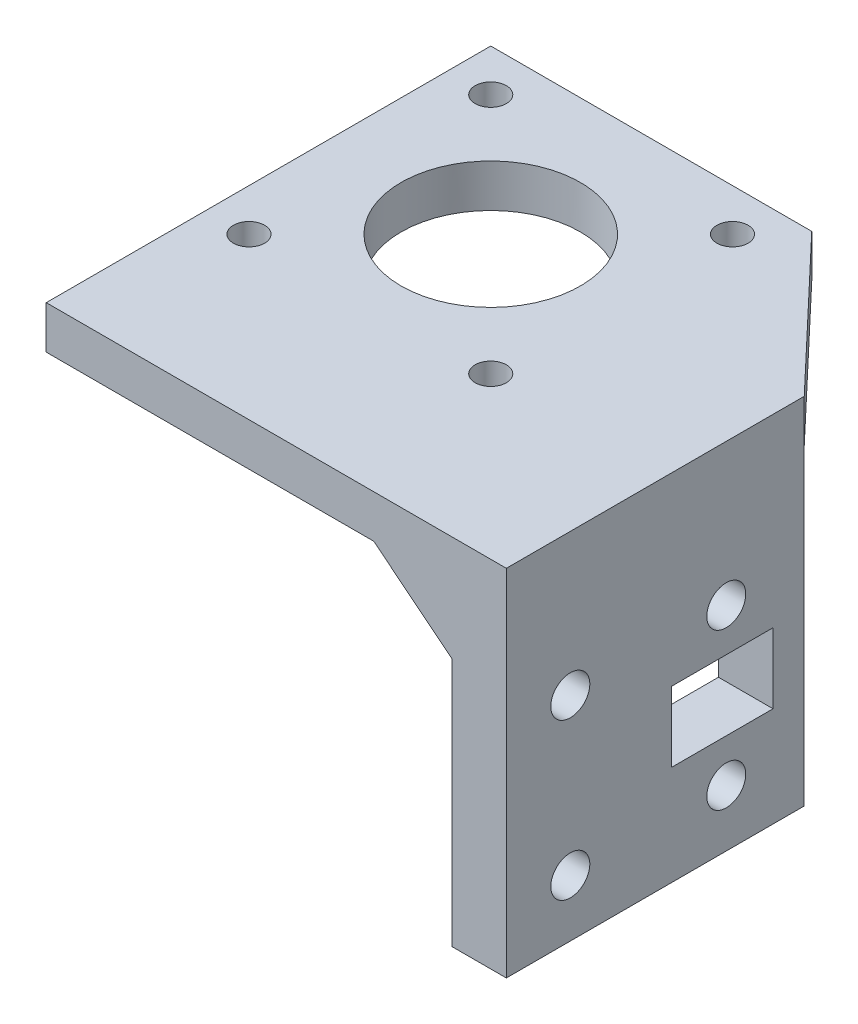
SolidWorks part; units mm, degrees
ref_plane "Front Plane" through (0, 0, 0) normal (0, 0, 1) x (1, 0, 0)
ref_plane "Top Plane" through (0, 0, 0) normal (0, 1, 0) x (1, 0, 0)
ref_plane "Right Plane" through (0, 0, 0) normal (1, 0, 0) x (0, 0, -1)
sketch "Sketch1" plane through (0, 0, 0) normal (0, 1, 0) x (1, 0, 0)
  line L1 (0, 0) -> (-59, 0)
  line L2 (0, 0) -> (0, -57)
  line L3 (0, -57) -> (-59, -57)
  line L4 (-59, 0) -> (-59, -57)
  point P5 (-59, 0)
  point P6 (0, 0)
  point P7 (0, 0)
  dimension "D1" = 57
  dimension "D2" = 59
extrude "Boss-Extrude1" add sketch "Sketch1" along normal blind 5.5
sketch "Sketch2" plane through (0, 5.5, 0) normal (0, 1, 0) x (1, 0, 0)
  line L0 (-59, 0) -> (-59, -57) construction
  line L1 (0, 0) -> (-59, 0) construction
  circle A0 centre (-53.6, -5.4) radius 2
  circle A1 centre (-22.6, -5.4) radius 2
  circle A2 centre (-53.6, -36.4) radius 2
  circle A3 centre (-22.6, -36.4) radius 2
  dimension "D5" = 31
  dimension "D9" = 4
  dimension "D10" = 4
  dimension "D11" = 4
  dimension "D12" = 4
  dimension "D8" = 31
  dimension "D1" = 5.4
  dimension "D2" = 5.4
  dimension "D3" = 5.4
  dimension "D4" = 31
  dimension "D6" = 5.4
  dimension "D7" = 31
extrude "Cut-Extrude1" cut sketch "Sketch2" against normal blind 10
sketch "Sketch4" plane through (0, 0, 0) normal (0, -1, 0) x (-1, 0, 0)
  line L0 (59, -57) -> (0, -57) construction
  line L1 (0, 0) -> (7, 0)
  line L2 (0, 0) -> (0, -57)
  line L3 (0, -57) -> (7, -57)
  line L4 (7, 0) -> (7, -57)
  dimension "D1" = 7
extrude "Boss-Extrude3" add sketch "Sketch4" along normal blind 40
sketch "Sketch5" plane through (-7, 0, 0) normal (-1, 0, 0) x (0, 0, 1)
  line L0 (57, -40) -> (57, 0) construction
  line L1 (57, -40) -> (0, -40) construction
  circle A0 centre (48.8, -32.7) radius 2.5
  circle A1 centre (48.8, -12.7) radius 2.5
  circle A2 centre (28.8, -32.7) radius 2.5
  circle A3 centre (28.8, -12.7) radius 2.5
  dimension "D3" = 5
  dimension "D4" = 5
  dimension "D7" = 5
  dimension "D8" = 5
  dimension "D1" = 8.2
  dimension "D2" = 7.3
  dimension "D5" = 20
  dimension "D6" = 0
  dimension "D9" = 20
  dimension "D10" = 20
  dimension "D11" = 20
  dimension "D12" = 7.3
extrude "Cut-Extrude2" cut sketch "Sketch5" against normal blind 33
sketch "Sketch6" plane through (-7, 0, 0) normal (-1, 0, 0) x (0, 0, 1)
  line L0 (57, 0) -> (0, 0) construction
  line L1 (0, -40) -> (18.8, -40)
  line L2 (0, -40) -> (0, 0)
  line L3 (0, 0) -> (18.8, 0)
  line L4 (18.8, -40) -> (18.8, 0)
  circle A0 centre (28.8, -32.7) radius 2.5 construction
  dimension "D1" = 10
extrude "Cut-Extrude3" cut sketch "Sketch6" against normal blind 33
sketch "Sketch7" plane through (0, 0, 0) normal (0, -1, 0) x (-1, 0, 0)
  line L0 (0, 0) -> (0, -18.8)
  line L1 (0, -18.8) -> (17.8364, 0)
  line L2 (0, 0) -> (59, 0) construction
  line L3 (17.8364, 0) -> (0, 0)
extrude "Cut-Extrude4" cut sketch "Sketch7" against normal blind 33
sketch "Sketch8" plane through (0, 0, 57) normal (0, 0, 1) x (1, 0, 0)
  line L0 (-7, 0) -> (-7, -8)
  line L1 (-7, -40) -> (-7, 0) construction
  line L2 (-7, -8) -> (-17, 0)
  line L3 (-59, 0) -> (-7, 0) construction
  line L4 (-17, 0) -> (-7, 0)
  dimension "D1" = 8
  dimension "D2" = 10
extrude "Boss-Extrude6" add sketch "Sketch8" against normal up to vertex (38.2 mm away) up to point (-7, -40, 18.8)
sketch "Sketch10" plane through (-7, 0, 0) normal (-1, 0, 0) x (0, 0, 1)
  line L1 (22.8, -18.2) -> (35.8, -18.2)
  line L2 (22.8, -18.2) -> (22.8, -27.2)
  line L3 (22.8, -27.2) -> (35.8, -27.2)
  line L4 (35.8, -18.2) -> (35.8, -27.2)
  line L5 (18.8, -40) -> (18.8, -8) construction
  circle A0 centre (28.8, -32.7) radius 2.5 construction
  circle A1 centre (28.8, -12.7) radius 2.5 construction
  dimension "D1" = 5.5
  dimension "D2" = 7
  dimension "D3" = 5.5
  dimension "D4" = 4
extrude "Cut-Extrude8" cut sketch "Sketch10" against normal blind 10
sketch "Sketch11" plane through (0, 5.5, 0) normal (0, 1, 0) x (1, 0, 0)
  circle A0 centre (-38.1, -20.9) radius 11.5
  circle A1 centre (-22.6, -36.4) radius 2 construction
  circle A2 centre (-53.6, -36.4) radius 2 construction
  dimension "D3" = 23
  dimension "D1" = 15.5
  dimension "D2" = 15.5
extrude "Cut-Extrude9" cut sketch "Sketch11" against normal blind 10
